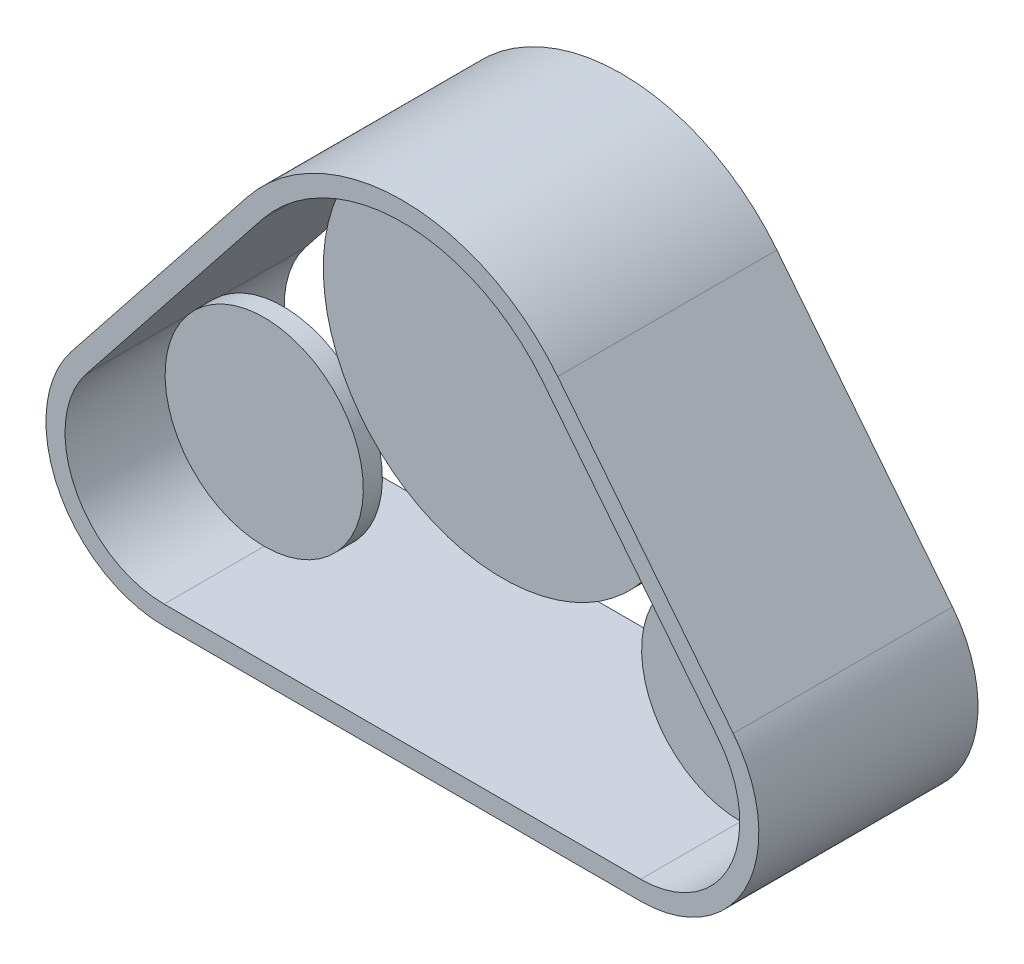
SolidWorks part; units mm, degrees
ref_plane "Piano frontale" through (0, 0, 0) normal (0, 0, 1) x (1, 0, 0)
ref_plane "Piano superiore" through (0, 0, 0) normal (0, 1, 0) x (1, 0, 0)
ref_plane "Piano destro" through (0, 0, 0) normal (1, 0, 0) x (0, 0, -1)
sketch "Schizzo1" plane through (0, 0, 0) normal (0, 0, 1) x (1, 0, 0)
  line L0 (-125, 0) -> (125, 0) construction
  line L1 (0, 90) -> (0, 0) construction
  circle A0 centre (-125, 0) radius 52
  circle A1 centre (125, 0) radius 52
  circle A2 centre (0, 90) radius 94
  point P6 (0, 0)
  dimension "D1" = 104
  dimension "D2" = 188
  dimension "D3" = 90
  dimension "D4" = 250
extrude "Estrusione-Estrusione1" add sketch "Schizzo1" along normal blind 10
sketch "Schizzo2" plane through (0, 0, 10) normal (0, 0, 1) x (1, 0, 0)
  line L0 (-165.7393, 32.3157) -> (-73.6442, 148.4169)
  line L1 (73.6442, 148.4169) -> (165.7393, 32.3157)
  line L2 (125, -52) -> (-125, -52)
  circle A0 centre (-125, 0) radius 52 construction
  circle A1 centre (125, 0) radius 52 construction
  circle A2 centre (0, 90) radius 94 construction
  arc A3 (-165.7393, 32.3157) -> (-125, -52) centre (-125, 0) ccw
  arc A4 (125, -52) -> (165.7393, 32.3157) centre (125, 0) ccw
  arc A5 (73.6442, 148.4169) -> (-73.6442, 148.4169) centre (0, 90) ccw
  point P1 (-69.1763, 153.6446)
extrude "Estrusione-Sottile1" add sketch "Schizzo2" along normal blind 52.5 and the other way blind 62.5 thin thin type one direction wall 10
